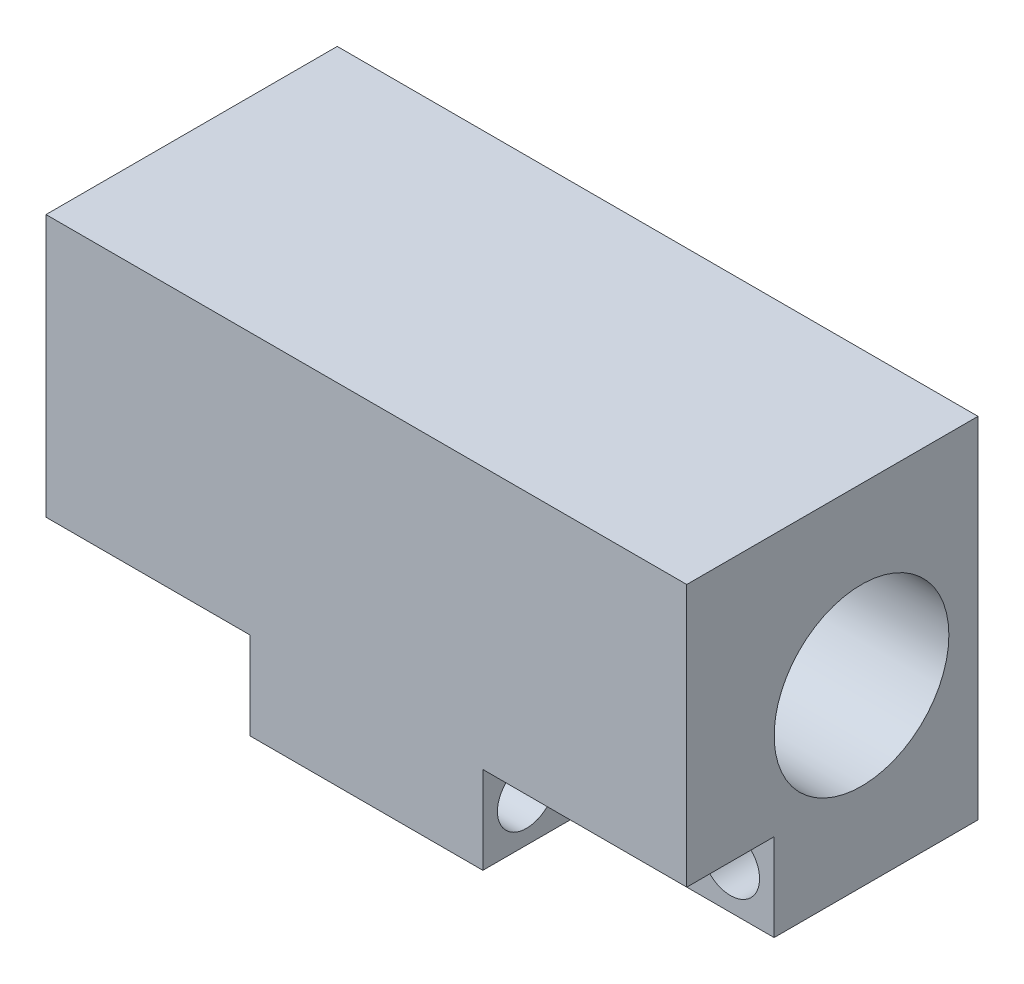
SolidWorks part; units mm, degrees
ref_plane "Front Plane" through (0, 0, 0) normal (0, 0, 1) x (1, 0, 0)
ref_plane "Top Plane" through (0, 0, 0) normal (0, 1, 0) x (1, 0, 0)
ref_plane "Right Plane" through (0, 0, 0) normal (1, 0, 0) x (0, 0, -1)
sketch "Sketch2" plane through (0, 0, 0) normal (0, 1, 0) x (1, 0, 0)
  line L4 (0, 10) -> (11, 10)
  line L5 (11, 10) -> (11, 0)
  line L7 (11, 0) -> (-11, 0)
  line L8 (-11, 0) -> (-11, 10)
  line L9 (-11, 10) -> (0, 10)
  point P14 (0, 0)
  dimension "D4" = 22
  dimension "D5" = 10
extrude "Boss-Extrude1" add sketch "Sketch2" along normal blind 12 contours L4 L5 L7 L8 L9
sketch "Sketch5" plane through (0, 0, -10) normal (0, 0, -1) x (-1, 0, 0)
  line L0 (11, 12) -> (11, 0) construction
  line L5 (11, 0) -> (-11, 0) construction
  circle A0 centre (9.5, 1.5) radius 1
  dimension "D1" = 2
  dimension "D5" = 1.5
  dimension "D6" = 1.5
extrude "Cut-Extrude1" cut sketch "Sketch5" against normal blind 10 contours A0
sketch "Sketch6" plane through (0, 0, 0) normal (1, 0, 0) x (0, 0, -1)
  line L0 (10, 0) -> (0, 0) construction
  line L1 (6, 9.2) -> (10, 9.2)
  line L2 (10, 12) -> (10, 0) construction
  line L3 (10, 9.2) -> (10, 2.8)
  line L4 (10, 2.8) -> (6, 2.8)
  arc A0 (6, 9.2) -> (6, 2.8) centre (6, 6) ccw
  dimension "D3" = 3.2
  dimension "D1" = 6
  dimension "D2" = 4
extrude "Cut-Extrude2" cut sketch "Sketch6" against normal blind 3 and the other way blind 3
sketch "Sketch7" plane through (3, 0, 0) normal (-1, 0, 0) x (0, 0, 1)
  circle A0 centre (-6, 6) radius 1.5
  arc A1 (-6, 2.8) -> (-6, 9.2) centre (-6, 6) ccw construction
  dimension "D1" = 3
extrude "Cut-Extrude3" cut sketch "Sketch7" against normal through all and the other way through all
sketch "Sketch9" plane through (-11, 0, 0) normal (-1, 0, 0) x (0, 0, 1)
  line L0 (0, 0) -> (-10, 0) construction
  line L2 (0, 12) -> (0, 0) construction
  circle A0 centre (-1.5, 1.5) radius 1
  dimension "D3" = 2
  dimension "D1" = 1.5
  dimension "D2" = 1.5
sketch "Sketch10" plane through (0, 0, 0) normal (0, 1, 0) x (1, 0, 0)
  line L1 (-11, 0) -> (-4, 0)
  line L2 (-11, 0) -> (-11, 3)
  line L3 (-11, 3) -> (-4, 3)
  line L4 (-4, 0) -> (-4, 3)
  dimension "D1" = 7
  dimension "D2" = 3
extrude "Cut-Extrude4" cut sketch "Sketch10" along normal blind 3
extrude "Cut-Extrude5" cut sketch "Sketch9" against normal through all contours A0
mirror "Mirror1" about plane through (0, 0, 0) normal (1, 0, 0) of "Cut-Extrude4", "Cut-Extrude1"
sketch "Sketch12" plane through (11, 0, 0) normal (1, 0, 0) x (0, 0, -1)
  circle A0 centre (6, 6) radius 3
  circle A1 centre (6, 6) radius 1.5 construction
  dimension "D1" = 6
extrude "Cut-Extrude6" cut sketch "Sketch12" against normal blind 6.5 contours A0
sketch "Sketch13" plane through (-11, 0, 0) normal (-1, 0, 0) x (0, 0, 1)
  line L1 (-9, 7.7321) -> (-9, 4.2679)
  line L2 (-9, 4.2679) -> (-6, 2.5359)
  line L3 (-6, 2.5359) -> (-3, 4.2679)
  line L4 (-3, 4.2679) -> (-3, 7.7321)
  line L5 (-3, 7.7321) -> (-6, 9.4641)
  line L6 (-6, 9.4641) -> (-9, 7.7321)
  circle A0 centre (-6, 6) radius 3 construction
  circle A1 centre (-6, 6) radius 1.5 construction
  dimension "D1" = 6
extrude "Cut-Extrude7" cut sketch "Sketch13" against normal blind 6.5
